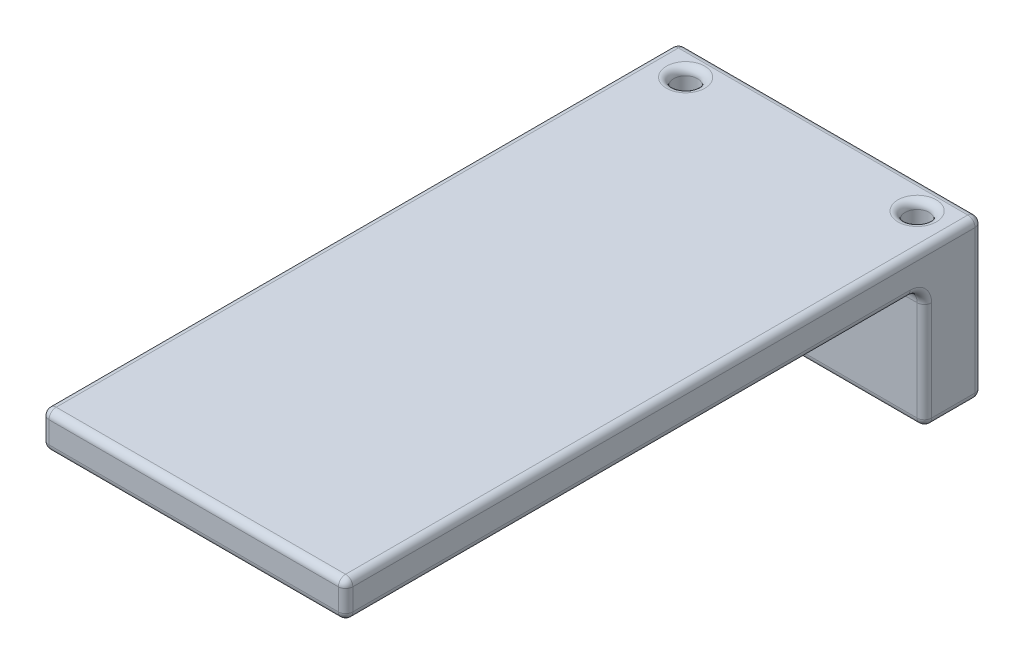
SolidWorks part; units mm, degrees
ref_plane "Front Plane" through (0, 0, 0) normal (0, 0, 1) x (1, 0, 0)
ref_plane "Top Plane" through (0, 0, 0) normal (0, 1, 0) x (1, 0, 0)
ref_plane "Right Plane" through (0, 0, 0) normal (1, 0, 0) x (0, 0, -1)
sketch "Sketch1" plane through (0, 0, 0) normal (0, 1, 0) x (1, 0, 0)
  line L1 (-21, -40) -> (21, -40)
  line L2 (-21, -40) -> (-21, 40)
  line L3 (-21, 40) -> (21, 40)
  line L4 (21, -40) -> (21, 40)
  line L5 (-21, -40) -> (21, 40) construction
  line L6 (-21, 40) -> (21, -40) construction
  point P0 (0, 0)
  dimension "D1" = 42
  dimension "D2" = 80
extrude "Boss-Extrude1" add sketch "Sketch1" along normal blind 5
sketch "Sketch2" plane through (0, 5, 0) normal (0, 1, 0) x (1, 0, 0)
  line L0 (21, -40) -> (21, 40) construction
  line L1 (-21, 40) -> (21, 40)
  line L2 (-21, 40) -> (-21, 48)
  line L3 (-21, 48) -> (21, 48)
  line L4 (21, 40) -> (21, 48)
  circle A0 centre (16, 44) radius 1.4 construction
  circle A1 centre (-16, 44) radius 1.4 construction
  circle A2 centre (16, 44) radius 1.4 construction
  circle A3 centre (-16, 44) radius 1.4 construction
  circle A4 centre (16, 44) radius 1.65
  circle A5 centre (-16, 44) radius 1.65
  dimension "D2" = 3.3
  dimension "D1" = 8
extrude "Boss-Extrude2" add sketch "Sketch2" against normal up to surface (21.8 mm away)
fillet "Fillet1" radius 2 1 edges at (0, 0, -40)
fillet "Fillet2" radius 1 23 edges at (-21, -9.4, -40) (-21, -0.5858, -39.4142) (0, 5, -48) (-21, -5.9, -48) (21, 5, -4) (21, -5.9, -48) (21, -9.4, -40) (21, -0.5858, -39.4142) (16, -16.8, -42.35) (-16, -16.8, -42.35) (0, -16.8, -40) (21, -16.8, -44) (0, -16.8, -48) (-21, -16.8, -44) (21, 0, 1) (-21, 0, 1) (-21, 2.5, 40) (0, 0, 40) (0, 5, 40) (21, 2.5, 40) (-21, 5, -4) (16, 5, -42.35) (-16, 5, -42.35)
